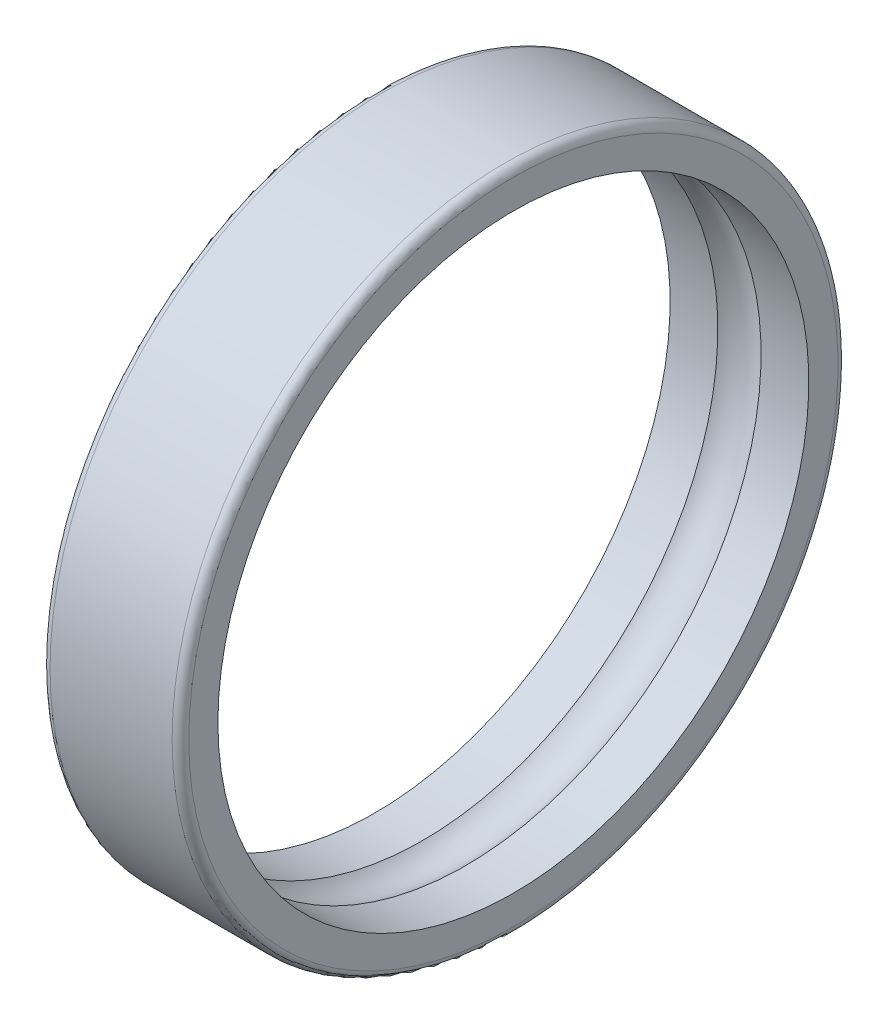
SolidWorks part; units mm, degrees
ref_plane "Front Plane" through (0, 0, 0) normal (0, 0, 1) x (1, 0, 0)
ref_plane "Top Plane" through (0, 0, 0) normal (0, 1, 0) x (1, 0, 0)
ref_plane "Right Plane" through (0, 0, 0) normal (1, 0, 0) x (0, 0, -1)
ref_plane "Plane1"
sketch "Sketch1" plane through (0, 0, 0) normal (0, 0, 1) x (1, 0, 0)
  line L0 (0, 11.7) -> (0, 10.65)
  line L1 (0, 10.65) -> (1.7207, 10.65)
  line L2 (3.2793, 10.65) -> (5, 10.65)
  line L3 (5, 10.65) -> (5, 11.7)
  line L4 (4.7, 12) -> (0.3, 12)
  line L5 (200, 0) -> (-200, 0) construction
  arc A0 (3.2793, 10.65) -> (1.7207, 10.65) centre (2.5, 9.75) ccw
  arc A1 (5, 11.7) -> (4.7, 12) centre (4.7, 11.7) ccw
  arc A2 (0.3, 12) -> (0, 11.7) centre (0.3, 11.7) ccw
revolve "Revolução1" add sketch "Sketch1" angle 360 about L5
